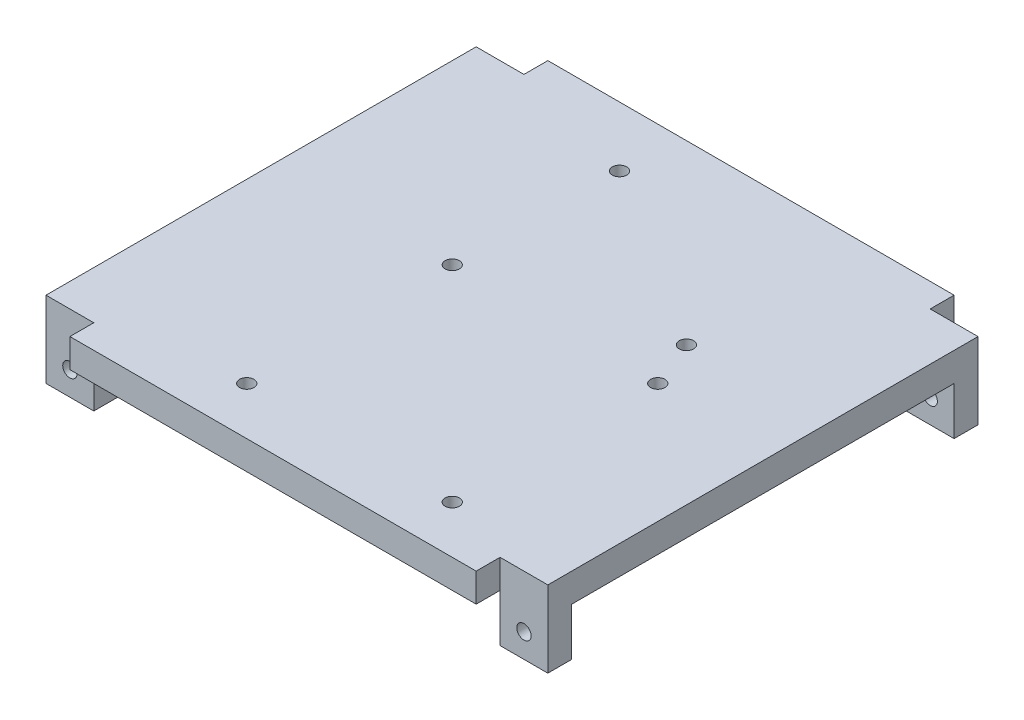
SolidWorks part; units mm, degrees
ref_plane "Front Plane" through (0, 0, 0) normal (0, 0, 1) x (1, 0, 0)
ref_plane "Top Plane" through (0, 0, 0) normal (0, 1, 0) x (1, 0, 0)
ref_plane "Right Plane" through (0, 0, 0) normal (1, 0, 0) x (0, 0, -1)
sketch "Sketch1" plane through (0, 0, 0) normal (0, 1, 0) x (1, 0, 0)
  line L1 (0, 0) -> (105, 0)
  line L2 (0, 0) -> (0, 100)
  line L3 (0, 100) -> (105, 100)
  line L4 (105, 0) -> (105, 100)
  dimension "D1" = 105
  dimension "D2" = 100
extrude "Boss-Extrude1" add sketch "Sketch1" along normal blind 6
sketch "Sketch2" plane through (0, 0, 0) normal (0, -1, 0) x (1, 0, 0)
  line L1 (105, -100) -> (95, -100)
  line L2 (105, -100) -> (105, -95)
  line L3 (105, -95) -> (95, -95)
  line L4 (95, -100) -> (95, -95)
  line L5 (0, -100) -> (10, -100)
  line L6 (0, -100) -> (0, -95)
  line L7 (0, -95) -> (10, -95)
  line L8 (10, -100) -> (10, -95)
  line L9 (105, 0) -> (95, 0)
  line L10 (105, 0) -> (105, -5)
  line L11 (105, -5) -> (95, -5)
  line L12 (95, 0) -> (95, -5)
  line L13 (0, 0) -> (10, 0)
  line L14 (0, 0) -> (0, -5)
  line L15 (0, -5) -> (10, -5)
  line L16 (10, 0) -> (10, -5)
  dimension "D1" = 10
  dimension "D2" = 5
extrude "Cut-Extrude1" cut sketch "Sketch2" against normal blind 10
sketch "Sketch3" plane through (0, 0, 0) normal (0, -1, 0) x (-1, 0, 0)
  line L1 (-105, 95) -> (-95, 95)
  line L2 (-105, 95) -> (-105, 90)
  line L3 (-105, 90) -> (-95, 90)
  line L4 (-95, 95) -> (-95, 90)
  line L5 (-105, 5) -> (-95, 5)
  line L6 (-105, 5) -> (-105, 10)
  line L7 (-105, 10) -> (-95, 10)
  line L8 (-95, 5) -> (-95, 10)
  line L9 (0, 5) -> (-10, 5)
  line L10 (0, 5) -> (0, 10)
  line L11 (0, 10) -> (-10, 10)
  line L12 (-10, 5) -> (-10, 10)
  line L13 (0, 95) -> (-10, 95)
  line L14 (0, 95) -> (0, 90)
  line L15 (0, 90) -> (-10, 90)
  line L16 (-10, 95) -> (-10, 90)
  dimension "D1" = 10
  dimension "D2" = 5
extrude "Boss-Extrude2" add sketch "Sketch3" along normal blind 10
sketch "Sketch4" plane through (0, 0, -95) normal (0, 0, -1) x (-1, 0, 0)
  line L0 (-105, 6) -> (-105, -10) construction
  line L1 (-95, -10) -> (-105, -10) construction
  line L2 (0, -10) -> (-10, -10) construction
  line L3 (-10, -10) -> (-10, 0) construction
  circle A0 centre (-100, -5) radius 1.5
  circle A1 centre (-5, -5) radius 1.5
  dimension "D1" = 5
  dimension "D2" = 5
  dimension "D3" = 3
  dimension "D4" = 5
  dimension "D5" = 5
extrude "Cut-Extrude2" cut sketch "Sketch4" against normal through all
sketch "Sketch5" plane through (0, 0, 0) normal (0, -1, 0) x (-1, 0, 0)
  line L0 (-10, 0) -> (-95, 0) construction
  line L1 (-105, 10) -> (-105, 90) construction
  circle A0 centre (-37, 10) radius 1.5
  circle A1 centre (-37, 53) radius 1.5
  circle A2 centre (-80, 53) radius 1.5
  circle A3 centre (-80, 10) radius 1.5
  dimension "D2" = 25
  dimension "D3" = 43
  dimension "D4" = 43
  dimension "D5" = 3
  dimension "D1" = 10
extrude "Cut-Extrude4" cut sketch "Sketch5" against normal blind 6
sketch "Sketch6" plane through (0, 0, 0) normal (0, -1, 0) x (-1, 0, 0)
  line L3 (-105, 10) -> (-105, 90) construction
  circle A0 centre (-37.5, 87.5) radius 1.5
  circle A1 centre (-76, 63) radius 1.5
  circle A2 centre (-80, 53) radius 1.5 construction
  dimension "D1" = 24.5
  dimension "D2" = 3
  dimension "D3" = 38.5
  dimension "D4" = 10
  dimension "D5" = 29
extrude "Cut-Extrude5" cut sketch "Sketch6" against normal blind 6
